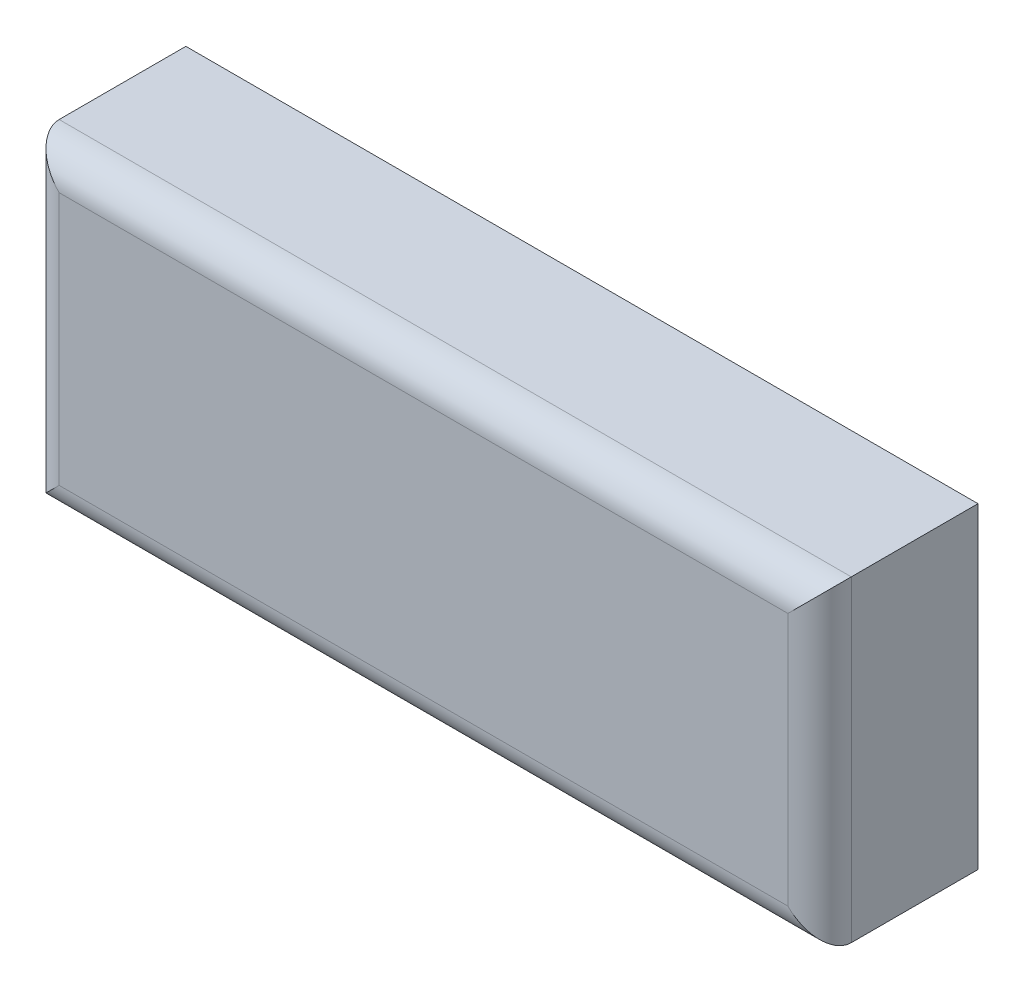
SolidWorks part; units mm, degrees
ref_plane "前视基准面" through (0, 0, 0) normal (0, 0, 1) x (1, 0, 0)
ref_plane "上视基准面" through (0, 0, 0) normal (0, 1, 0) x (1, 0, 0)
ref_plane "右视基准面" through (0, 0, 0) normal (1, 0, 0) x (0, 0, -1)
sketch "草图1" plane through (0, 0, 0) normal (0, 0, 1) x (1, 0, 0)
  line L1 (-35.9732, 15.6428) -> (14.0268, 15.6428)
  line L2 (-35.9732, 15.6428) -> (-35.9732, -4.3572)
  line L3 (-35.9732, -4.3572) -> (14.0268, -4.3572)
  line L4 (14.0268, 15.6428) -> (14.0268, -4.3572)
  dimension "D1" = 20
  dimension "D2" = 50
extrude "凸台-拉伸1" add sketch "草图1" along normal blind 10
fillet "圆角1" radius 2 4 edges at (-10.9732, 15.6428, 10) (14.0268, 5.6428, 10) (-10.9732, -4.3572, 10) (-35.9732, 5.6428, 10)
sketch "草图2" plane through (0, 0, 0) normal (0, 0, -1) x (-1, 0, 0)
  line L0 (35.9732, -4.3572) -> (-14.0268, -4.3572) construction
  line L1 (-14.0268, -4.3572) -> (-14.0268, 15.6428) construction
  circle A0 centre (10.9732, 5.6428) radius 4
  dimension "D1" = 8
  dimension "D2" = 10
  dimension "D3" = 25
extrude "切除-拉伸1" cut sketch "草图2" against normal blind 5
